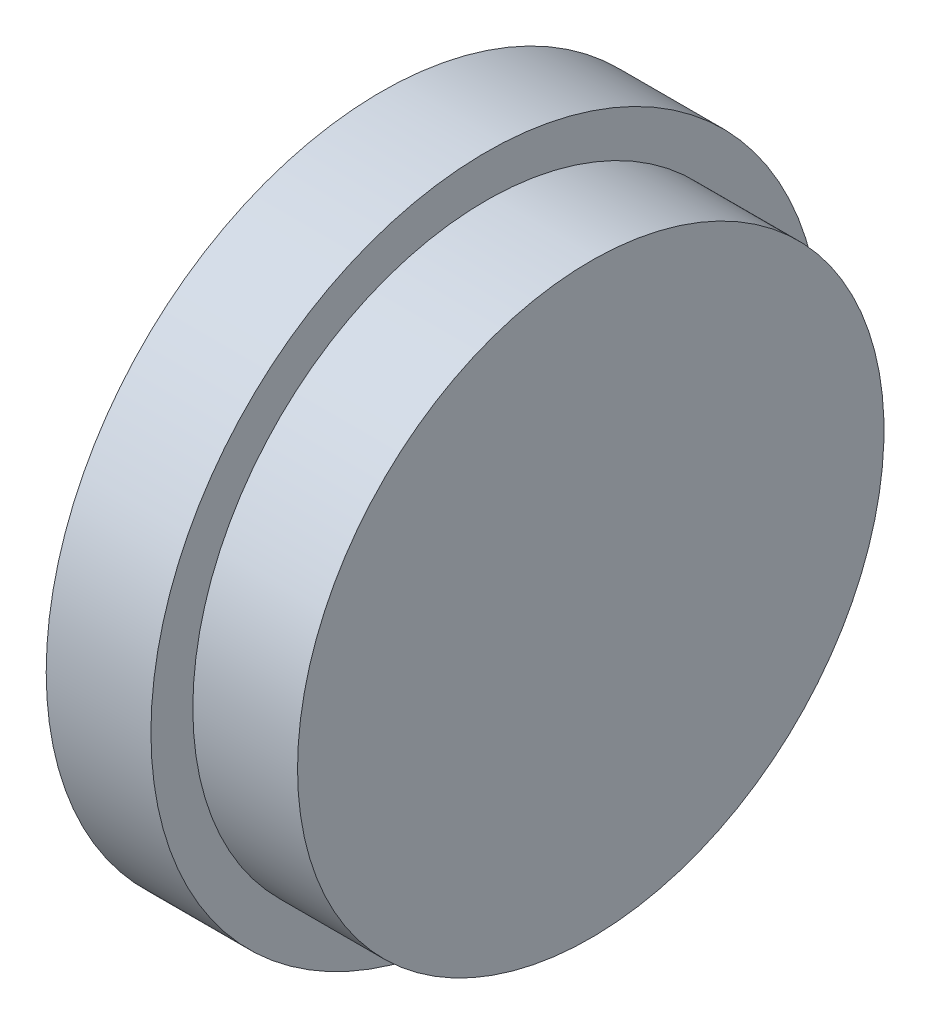
SolidWorks part; units mm, degrees
ref_plane "Спереди" through (0, 0, 0) normal (0, 0, 1) x (1, 0, 0)
ref_plane "Сверху" through (0, 0, 0) normal (0, 1, 0) x (1, 0, 0)
ref_plane "Справа" through (0, 0, 0) normal (1, 0, 0) x (0, 0, -1)
sketch "Эскиз1" plane through (0, 0, 0) normal (0, 0, 1) x (1, 0, 0)
  line L0 (0, 0) -> (16.8365, 0) construction
  line L1 (0, 0) -> (0, 8)
  line L2 (0, 8) -> (2.5, 8)
  line L3 (2.5, 8) -> (2.5, 7)
  line L4 (2.5, 7) -> (5, 7)
  line L5 (5, 7) -> (5, 0)
  line L6 (5, 0) -> (0, 0)
  dimension "D1" = 16
  dimension "D2" = 5
  dimension "D3" = 14
  dimension "D4" = 2.5
revolve "Повернуть1" add sketch "Эскиз1" angle 360 about L0
